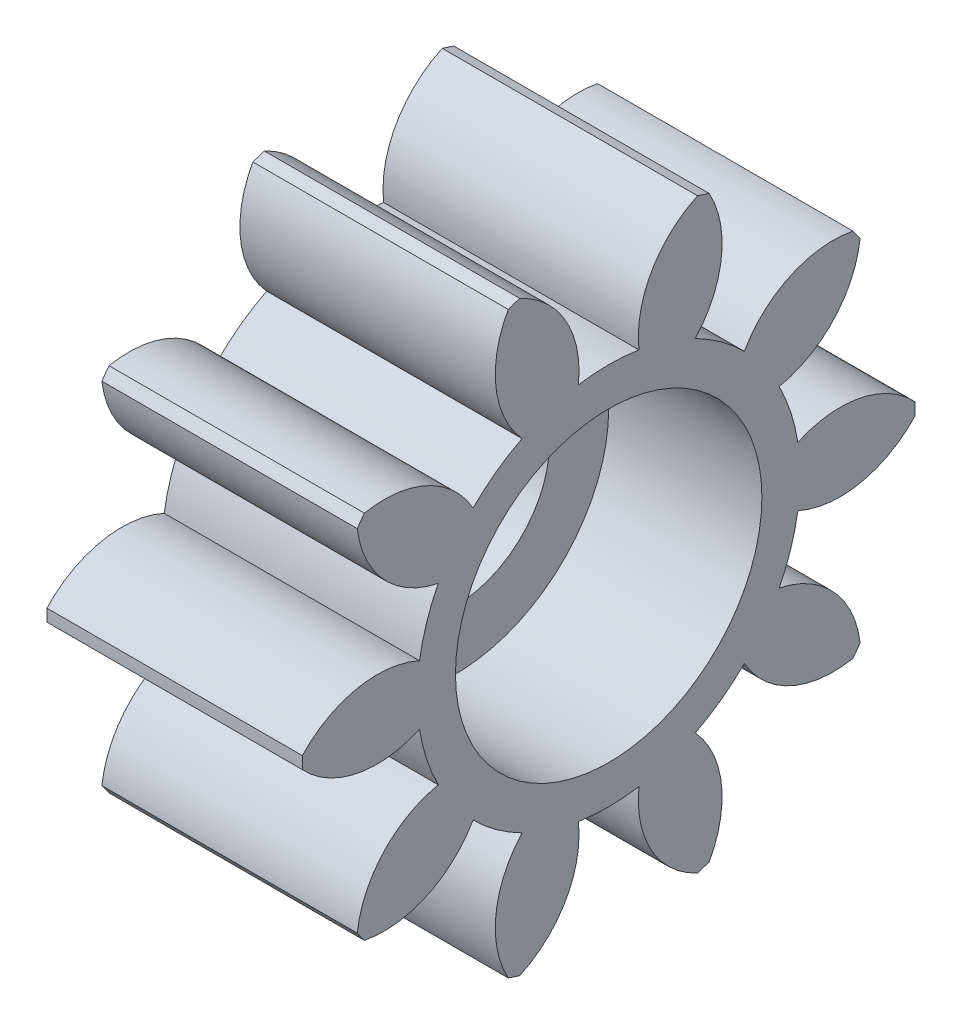
SolidWorks part; units mm, degrees
ref_plane "Plane1" through (0, 0, 0) normal (0, 0, 1) x (1, 0, 0)
ref_plane "Plane2" through (0, 0, 0) normal (0, 1, 0) x (1, 0, 0)
ref_plane "Plane3" through (0, 0, 0) normal (1, 0, 0) x (0, 0, -1)
sketch "HoldingSke" plane through (0, 0, 0) normal (0, 1, 0) x (1, 0, 0)
  line L0 (0, 0) -> (0.9848, -0.1736)
  line L1 (-15, 0) -> (100, 0) construction
  line L2 (0, 0) -> (-2.1039, 2.3779)
  line L3 (0, 0) -> (-11.863, 4.5341)
  line L4 (0, 0) -> (8.5048, 1.4996)
  line L5 (0, 0) -> (-46.8476, -17.4728)
  line L6 (0, 0) -> (-4.1448, -2.7965)
  line L7 (-2.1039, 2.3779) -> (8.6586, 51.2059)
  line L8 (-76.2, 54.61) -> (-75.7, 54.61)
  line L9 (-71.009, 38.7566) -> (-53.1078, 45.2721)
  line L10 (-76.2, 71.12) -> (104.1128, 71.12)
  line L11 (0, 0) -> (-5, 0)
  line L12 (-76.2, 101.6) -> (-76.162, 101.6)
  line L13 (24.9733, 27.94) -> (52.9518, 28.4284)
  line L14 (24.9733, 27.94) -> (24.9743, 27.94)
  line L15 (24.9733, 27.94) -> (100.4006, 29.5858)
  line L16 (-63.627, -1) -> (-12.827, -1)
  circle A0 centre (0, 0) radius 1.5
  circle A1 centre (0, 0) radius 3.749
  circle A2 centre (0, 0) radius 37.5
  circle A3 centre (0, 0) radius 1.5
  dimension "MHD" = 7.498
  dimension "Hub_dia" = 75
  dimension "Bore" = 3
  dimension "MBD" = 3
  dimension "Num_teeth" = 10
  dimension "Pitch" = 1
  dimension "Overall_len" = 50
  dimension "Show_teeth" = 10
  dimension "Thickness" = 5
  dimension "OAL" = 50.0001
  dimension "T_dim" = 0.5
  dimension "Ap" = 20
  dimension "H" = 19.05
  dimension "Pitch_radius" = 180.3128
  dimension "Width" = 5
  dimension "Backlash" = 0.038
  dimension "Addendum_fac" = 1
  dimension "Dedendum_fac" = 1.25
  dimension "Clearance_fac" = 0.25
  dimension "Dedendum_add" = 0.001
  dimension "Module" = 1
sketch "BasProSke" plane through (0, 0, 0) normal (0, 1, 0) x (1, 0, 0)
  line L0 (-10, 0) -> (60, 0) construction
  line L1 (0, 0) -> (0, 6)
  line L2 (0, 0) -> (5, 0)
  line L3 (5, 0) -> (5, 6)
  line L4 (5, 6) -> (0, 6)
  dimension "Thickness" = 5
  dimension "Diameter" = 12
revolve "Base-Revolve" add sketch "BasProSke" angle 360 about L0
sketch "TooCutSke" plane through (0, 0, 0) normal (1, 0, 0) x (0, 0, -1)
  line L1 (0, 0) -> (0, 107) construction
  line L2 (0, 0) -> (-0.8485, 4.9275) construction
  line L3 (0, 0) -> (-3.0584, 9.4126) construction
  line L4 (-0.8485, 4.9275) -> (-1.5292, 4.7063) construction
  arc A0 (0.5928, 3.7018) -> (-0.5928, 3.7018) centre (0, 0) ccw
  arc A1 (1.7758, 5.7578) -> (-1.7758, 5.7578) centre (0, 0) ccw
  circle A2 centre (0, 0) radius 5 construction
  circle A3 centre (0, 0) radius 4.6985 construction
  arc A4 (-0.5928, 3.7018) -> (-1.7758, 5.7578) centre (-2.5801, 3.9267) ccw
  arc A5 (1.7758, 5.7578) -> (0.5928, 3.7018) centre (2.5801, 3.9267) ccw
  dimension "Root_dia" = 7.498
  dimension "Overcut_dia" = 12.0508
  dimension "Pitch_dia" = 10
  dimension "Base_dia" = 9.3969
  dimension "Flank_rad" = 2
  dimension "Half_ang" = 18
  dimension "Half_CT" = 0.7157
extrude "ToothCut" cut sketch "TooCutSke" along normal through all
fillet "Breaks" [suppressed] radius 0.02
fillet "RootFillets" [suppressed] radius 0.251
pattern_circular "TeethCuts" count 10 every 36 about axis through (-10, 0, 0) along (1, 0, 0) of "ToothCut", "RootFillets", "Breaks"
sketch "HubNeaOneSke" plane through (0, 0, 0) normal (-1, 0, 0) x (0, 0, 1)
  circle A0 centre (0, 0) radius 3.749
  dimension "Diameter" = 7.498
extrude "HubNearOne" [suppressed] add sketch "HubNeaOneSke" along normal blind 45.0001
sketch "HubNeaBotSke" plane through (0, 0, 0) normal (-1, 0, 0) x (0, 0, 1)
  circle A0 centre (0, 0) radius 3.749
  dimension "Diameter" = 7.498
extrude "HubNearBoth" [suppressed] add sketch "HubNeaBotSke" along normal blind 22.5
ref_plane "FarPln" through (5, 0, 0) normal (1, 0, 0) x (0, 0, -1)
sketch "HubFarSke" plane through (5, 0, 0) normal (1, 0, 0) x (0, 0, -1)
  circle A0 centre (0, 0) radius 3.749
  dimension "Diameter" = 7.498
extrude "HubFar" [suppressed] add sketch "HubFarSke" along normal blind 22.5
sketch "BorSke" plane through (0, 0, 0) normal (1, 0, 0) x (0, 0, -1)
  circle A0 centre (0, 0) radius 1.5
  dimension "Diameter" = 3
extrude "Bore" cut sketch "BorSke" along normal mid plane 100.0001
sketch "KeySke" plane through (0, 0, 0) normal (1, 0, 0) x (0, 0, -1)
  line L0 (-0.6, 0) -> (-0.6, 2)
  line L1 (-0.6, 2) -> (0.6, 2)
  line L2 (0.6, 2) -> (0.6, 0)
  line L3 (0, 0) -> (0, 34) construction
  line L4 (-0.6, 0) -> (0.6, 0)
  dimension "Offset" = 2
  dimension "Width" = 1.2
extrude "Keyway" [suppressed] cut sketch "KeySke" along normal mid plane 100.0001
pattern_circular "Keyway2" [suppressed] count 2 every 90 about axis through (-10, 0, 0) along (1, 0, 0)
sketch "Sketch1" plane through (5, 0, 0) normal (1, 0, 0) x (0, 0, -1)
  circle A0 centre (0, 0) radius 3
extrude "Cut-Extrude1" cut sketch "Sketch1" against normal blind 3
scale "Scale1" scale about centroid uniform scaling yes scale factor 0.95
sketch "Sketch2" plane through (2.0128, 0, 0) normal (1, 0, 0) x (0, 0, -1)
  circle A0 centre (0, 0) radius 1.75
extrude "Cut-Extrude2" cut sketch "Sketch2" against normal through all
equation "' \"Module@HoldingSke\" = 6.35"
equation "' \"Num_teeth@HoldingSke\" = 12"
equation "' \"Ap@HoldingSke\" =  20"
equation "' \"Ap@HoldingSke\" = 20"
equation "' \"Width@HoldingSke\" = 0.5 * 25.4"
equation "' \"Hub_dia@HoldingSke\"= 1 * 25.4"
equation "' \"Hub_dia@HoldingSke\" = 1 * 25.4"
equation "' \"Overall_len@HoldingSke\" = 1.0 * 25.4"
equation "' \"Bore@HoldingSke\" = 0.75 * 25.4"
equation "' \"T_dim@HoldingSke\" = 0.1 * 25.4"
equation "' \"Width@KeySke\" = 0.25 * 25.4"
equation "' \"Show_teeth@HoldingSke\" = 13"
equation "' \"Backlash@HoldingSke\" = 0.009 * 25.4"
equation "' \"Addendum_fac@HoldingSke\" = 1.0"
equation "' \"Dedendum_fac@HoldingSke\" = 1.25"
equation "' \"Dedendum_add@HoldingSke\" = 0.00005 * 25.4"
equation "' \"Clearance_fac@HoldingSke\" = 0.25"
equation "\"Pitch@HoldingSke\" = 1 / \"Module@HoldingSke\""
equation "\"Overcut_dia@TooCutSke\" = (\"Num_teeth@HoldingSke\" + 2 * \"Addendum_fac@HoldingSke\") / \"Pitch@HoldingSke\" + 0.002 * 25.4"
equation "\"Pitch_dia@TooCutSke\" = \"Num_teeth@HoldingSke\" / \"Pitch@HoldingSke\""
equation "\"Base_dia@TooCutSke\" = \"Num_teeth@HoldingSke\" / \"Pitch@HoldingSke\" * cos((\"Ap@HoldingSke\"  * 3.14159265 / 180))"
equation "\"Root_dia@TooCutSke\" = (\"Num_teeth@HoldingSke\" + 2) / \"Pitch@HoldingSke\" - 2 * (\"Addendum_fac@HoldingSke\" + \"Dedendum_fac@HoldingSke\") / \"Pitch@HoldingSke\" - \"Dedendum_add@HoldingSke\" * 2"
equation "\"Half_ang@TooCutSke\" = 180 / \"Num_teeth@HoldingSke\""
equation "\"Half_CT@TooCutSke\" = \"Num_teeth@HoldingSke\" / \"Pitch@HoldingSke\" * sin((3.14159265 / 2 / \"Num_teeth@HoldingSke\")) / 2 - 7 * \"Backlash@HoldingSke\" / 4"
equation "\"Flank_rad@TooCutSke\" = \"Num_teeth@HoldingSke\" / \"Pitch@HoldingSke\" / 5"
equation "\"Radius@RootFillets\" = \"Clearance_fac@HoldingSke\" / \"Pitch@HoldingSke\" + \"Dedendum_add@HoldingSke\""
equation "\"Break_rad@Breaks\" = 0.02 / \"Pitch@HoldingSke\""
equation "\"Thickness@HoldingSke\" = \"Width@HoldingSke\""
equation "\"OAL@HoldingSke\" = \"Thickness@HoldingSke\""
equation "\"MHD@HoldingSke\" = (\"Num_teeth@HoldingSke\" + 2) / \"Pitch@HoldingSke\" - 2 * (\"Addendum_fac@HoldingSke\" + \"Dedendum_fac@HoldingSke\")  / \"Pitch@HoldingSke\" - \"Dedendum_add@HoldingSke\" * 2"
equation "\"MBD@HoldingSke\" = (\"Num_teeth@HoldingSke\" + 2) / \"Pitch@HoldingSke\" - 2 * (\"Addendum_fac@HoldingSke\" + \"Dedendum_fac@HoldingSke\")  / \"Pitch@HoldingSke\" - \"Dedendum_add@HoldingSke\" * 2 - 0.002 * 25.4"
equation "\"MHD@HoldingSke\" = ((sgn( \"MHD@HoldingSke\" - \"Hub_dia@HoldingSke\" )-1)*( \"MHD@HoldingSke\" - \"Hub_dia@HoldingSke\" ))/-2+ \"Hub_dia@HoldingSke\""
equation "\"MBD@HoldingSke\" = ((sgn( \"MBD@HoldingSke\" - \"Bore@HoldingSke\" )-1)*( \"MBD@HoldingSke\" - \"Bore@HoldingSke\" ))/-2+ \"Bore@HoldingSke\""
equation "\"OAL@HoldingSke\" = ((sgn( \"OAL@HoldingSke\" - \"Overall_len@HoldingSke\" )+1)*( \"OAL@HoldingSke\" - \"Overall_len@HoldingSke\" ))/2 + \"Overall_len@HoldingSke\" + 0.000002 * 25.4"
equation "\"Num_teeth@TeethCuts\" = int( \"Show_teeth@HoldingSke\" ) + 1"
equation "\"Num_teeth@TeethCuts\" = ((sgn( \"Num_teeth@TeethCuts\" - \"Num_teeth@HoldingSke\" )-1)*( \"Num_teeth@TeethCuts\" - \"Num_teeth@HoldingSke\" ))/-2+ \"Num_teeth@HoldingSke\""
equation "\"Num_teeth@TeethCuts\" = ((sgn( \"Num_teeth@TeethCuts\" - 2.0)+1)*( \"Num_teeth@TeethCuts\" - 2.0))/2 +2.0"
equation "\"Angle@TeethCuts\" = 360.0 / \"Num_teeth@HoldingSke\""
equation "\"Diameter@BasProSke\" = (\"Num_teeth@HoldingSke\" + 2 * \"Addendum_fac@HoldingSke\") / \"Pitch@HoldingSke\""
equation "\"Thickness@BasProSke\"  = \"Thickness@HoldingSke\""
equation "' \"Fillet_rad@BasProSke\" =  \"Thickness@HoldingSke\" * 0.05"
equation "' \"Fillet_rad@BasProSke\" = \"Thickness@HoldingSke\" * 0.05"
equation "\"MHD@HoldingSke\" = ((sgn( \"MHD@HoldingSke\" - \"Root_dia@TooCutSke\" )-1)*( \"MHD@HoldingSke\" - \"Root_dia@TooCutSke\" ))/-2+ \"Root_dia@TooCutSke\""
equation "\"Diameter@HubNeaOneSke\" = \"MHD@HoldingSke\""
equation "\"Length@HubNearOne\" = \"OAL@HoldingSke\" - \"Thickness@BasProSke\""
equation "\"Diameter@HubNeaBotSke\" = \"MHD@HoldingSke\""
equation "\"Length@HubNearBoth\" = ( \"OAL@HoldingSke\" - \"Thickness@BasProSke\" ) / 2.0"
equation "\"Thickness@FarPln\" = \"Thickness@BasProSke\""
equation "\"Diameter@HubFarSke\" = \"MHD@HoldingSke\""
equation "\"Length@HubFar\" = ( \"OAL@HoldingSke\" - \"Thickness@BasProSke\" ) / 2.0"
equation "\"Diameter@BorSke\" = \"MBD@HoldingSke\""
equation "\"D1@Bore\" = \"OAL@HoldingSke\" * 2.0"
equation "\"D1@Keyway\" = \"OAL@HoldingSke\" * 2.0"
equation "\"Offset@KeySke\" = \"T_dim@HoldingSke\" + \"MBD@HoldingSke\" / 2.0"
